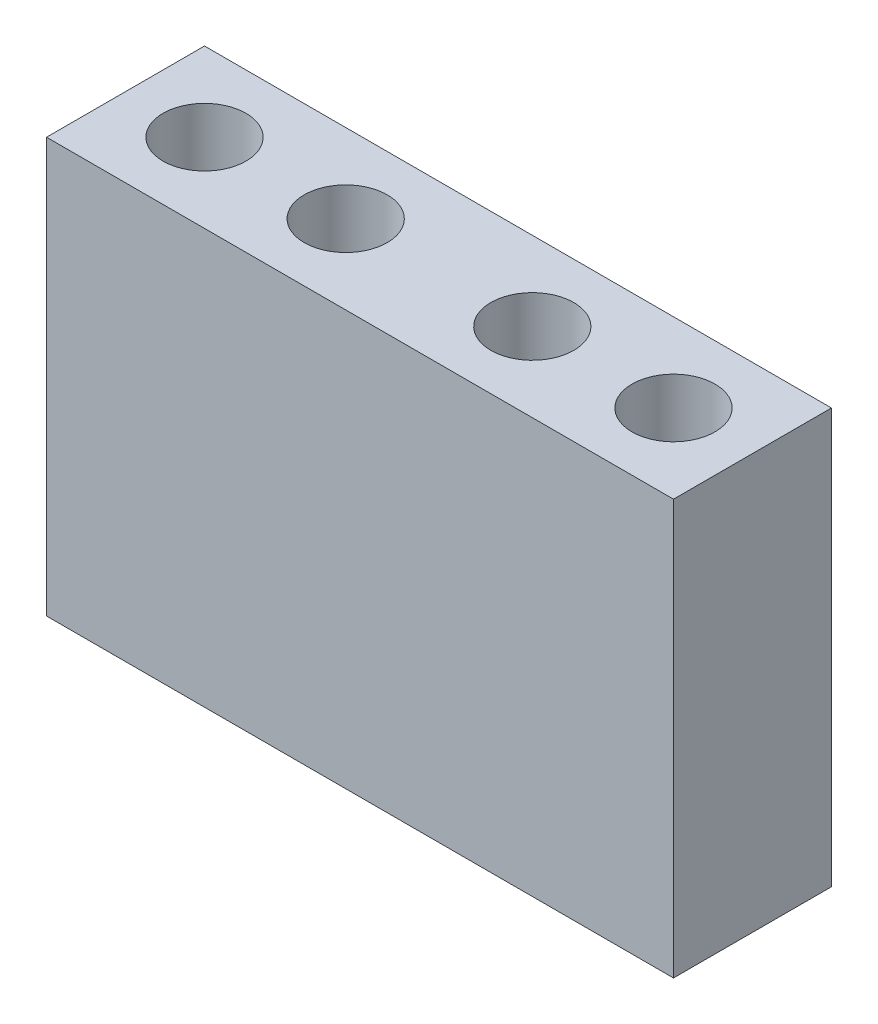
SolidWorks part; units mm, degrees
ref_plane "Front Plane" through (0, 0, 0) normal (0, 0, 1) x (1, 0, 0)
ref_plane "Top Plane" through (0, 0, 0) normal (0, 1, 0) x (1, 0, 0)
ref_plane "Right Plane" through (0, 0, 0) normal (1, 0, 0) x (0, 0, -1)
sketch "Sketch1" plane through (0, 0, 0) normal (0, 1, 0) x (1, 0, 0)
  line L1 (-11.15, 4) -> (20.6, 4)
  line L2 (-11.15, 4) -> (-11.15, -4)
  line L3 (-11.15, -4) -> (20.6, -4)
  line L4 (20.6, 4) -> (20.6, -4)
  circle A0 centre (0, 0) radius 2.1
  circle A1 centre (-7.15, 0) radius 2.1
  circle A2 centre (9.45, 0) radius 2.1
  circle A3 centre (16.6, 0) radius 2.1
  dimension "D1" = 4.2
  dimension "D2" = 7.15
  dimension "D3" = 4.2
  dimension "D6" = 4
  dimension "D8" = 4
  dimension "D4" = 7.15
  dimension "D9" = 9.45
  dimension "D5" = 4
  dimension "D7" = 4
extrude "Boss-Extrude1" add sketch "Sketch1" along normal blind 21
sketch "Sketch2" plane through (0, 0, 4) normal (0, 0, 1) x (1, 0, 0)
  line L0 (14.4, 21) -> (3.3384, 10)
  line L1 (-11.15, 21) -> (20.6, 21) construction
  line L2 (-11.15, 0) -> (20.6, 0) construction
  line L4 (20.6, 21) -> (20.6, 0) construction
  line L5 (3.3384, 10) -> (-7.6003, 21)
  line L6 (-7.6003, 21) -> (14.4, 21)
  dimension "D1" = 44.84
  dimension "D2" = 6.2
  dimension "D3" = 10
  dimension "D4" = 45.16
extrude "Cut-Extrude1" [suppressed] cut sketch "Sketch2" against normal blind 17.5
sketch "Sketch4" plane through (20.6, 0, 0) normal (1, 0, 0) x (0, 0, -1)
  line L0 (-4, 0) -> (4, 0) construction
  line L1 (4, 21) -> (4, 0) construction
  circle A0 centre (0, 4) radius 2.1
  dimension "D1" = 4.2
  dimension "D2" = 4
  dimension "D3" = 4
extrude "Cut-Extrude3" cut sketch "Sketch4" against normal blind 38.5
sketch "Sketch6" plane through (0, 0, 0) normal (0, -1, 0) x (1, 0, 0)
  circle A0 centre (-7.15, 0) radius 2.1
  circle A1 centre (0, 0) radius 2.1
  circle A2 centre (9.45, 0) radius 2.1
  circle A3 centre (16.6, 0) radius 2.1
extrude "Boss-Extrude3" add sketch "Sketch6" against normal blind 2
sketch "Sketch7" plane through (20.6, 0, 0) normal (1, 0, 0) x (0, 0, -1)
  circle A0 centre (0, 4) radius 2.1
extrude "Boss-Extrude4" add sketch "Sketch7" against normal blind 2
